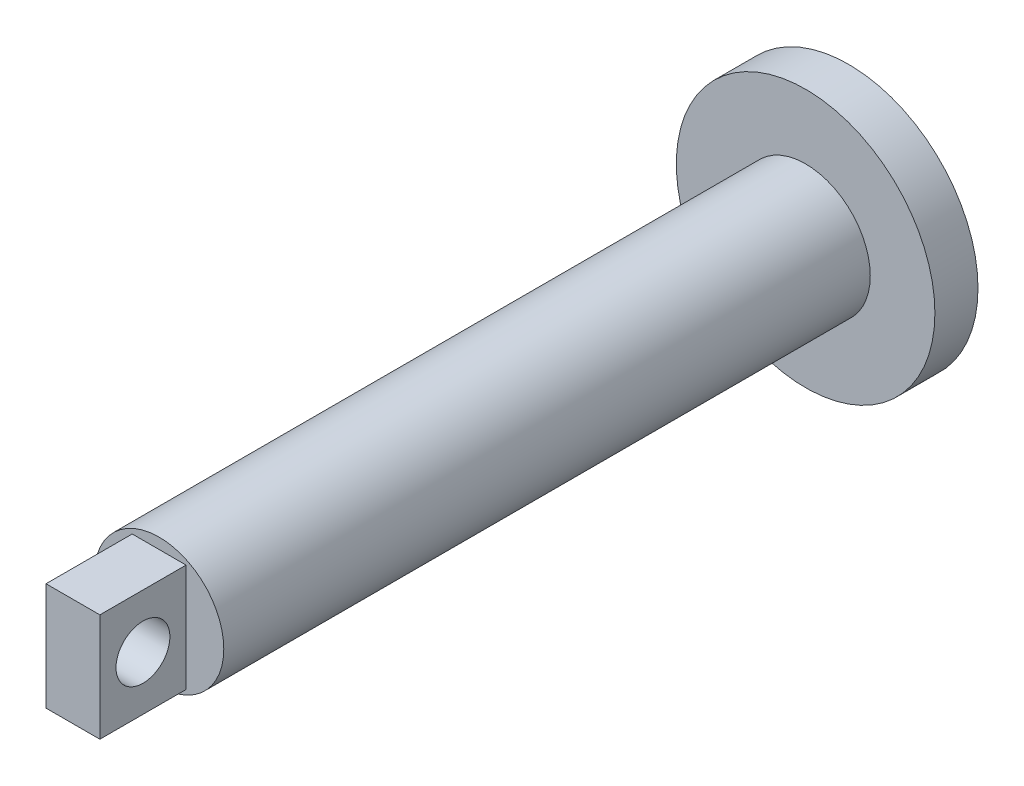
SolidWorks part; units mm, degrees
ref_plane "Front Plane" through (0, 0, 0) normal (0, 0, 1) x (1, 0, 0)
ref_plane "Top Plane" through (0, 0, 0) normal (0, 1, 0) x (1, 0, 0)
ref_plane "Right Plane" through (0, 0, 0) normal (1, 0, 0) x (0, 0, -1)
sketch "Sketch1" plane through (0, 0, 0) normal (0, 0, 1) x (1, 0, 0)
  circle A0 centre (0, 0) radius 6
  dimension "D1" = 12
extrude "Boss-Extrude1" add sketch "Sketch1" along normal blind 2
sketch "Sketch2" plane through (0, 0, 2) normal (0, 0, 1) x (1, 0, 0)
  circle A0 centre (0, 0) radius 3
  dimension "D1" = 6
extrude "Boss-Extrude2" add sketch "Sketch2" along normal blind 30
sketch "Sketch3" plane through (0, 0, 32) normal (0, 0, 1) x (1, 0, 0)
  line L1 (-1.25, -2.5) -> (1.25, -2.5)
  line L2 (-1.25, -2.5) -> (-1.25, 2.5)
  line L3 (-1.25, 2.5) -> (1.25, 2.5)
  line L4 (1.25, -2.5) -> (1.25, 2.5)
  line L5 (-1.25, -2.5) -> (1.25, 2.5) construction
  line L6 (-1.25, 2.5) -> (1.25, -2.5) construction
  point P0 (0, 0)
  dimension "D1" = 5
  dimension "D2" = 2.5
extrude "Boss-Extrude3" add sketch "Sketch3" along normal blind 4
sketch "Sketch4" plane through (-1.25, 0, 0) normal (-1, 0, 0) x (0, 0, 1)
  line L0 (36, 2.5) -> (36, -2.5) construction
  line L3 (36, -2.5) -> (32, -2.5) construction
  circle A0 centre (34, 0) radius 1.25
  dimension "D1" = 2.5
  dimension "D2" = 2
  dimension "D3" = 2.5
extrude "Cut-Extrude1" cut sketch "Sketch4" against normal up to next
